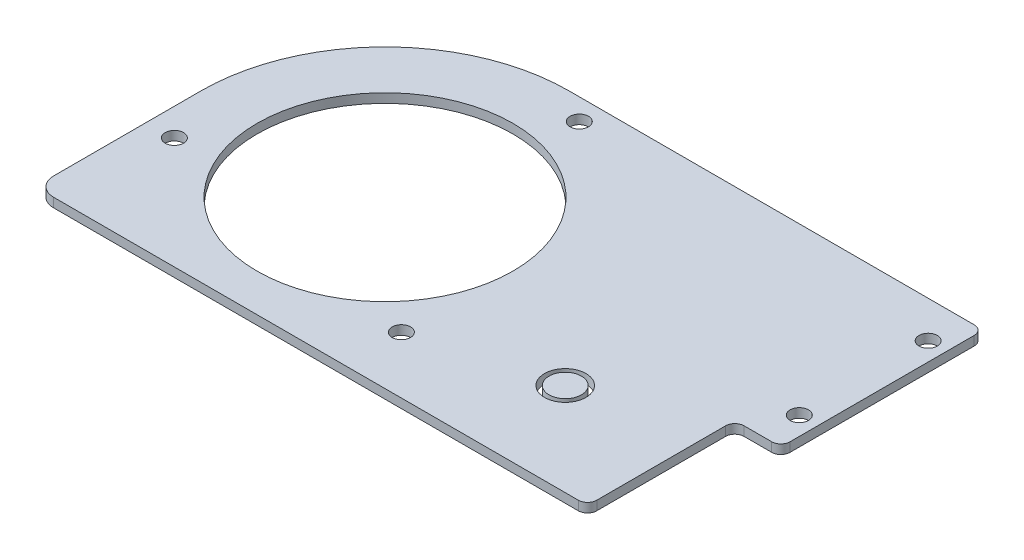
SolidWorks part; units mm, degrees
ref_plane "Front Plane" through (0, 0, 0) normal (0, 0, 1) x (1, 0, 0)
ref_plane "Top Plane" through (0, 0, 0) normal (0, 1, 0) x (1, 0, 0)
ref_plane "Right Plane" through (0, 0, 0) normal (1, 0, 0) x (0, 0, -1)
sketch "Sketch1" plane through (0, 0, 0) normal (0, 1, 0) x (1, 0, 0)
  line L0 (0, 114.3) -> (0, -101.6) construction
  line L1 (279.4, 127) -> (0, 127)
  line L2 (285.75, 120.65) -> (285.75, -6.35)
  line L3 (247.65, -114.3) -> (-114.3, -114.3)
  line L4 (-127, 0) -> (-127, -101.6)
  line L5 (260.35, -12.7) -> (279.4, -12.7)
  line L6 (273.05, -12.7) -> (273.05, 127) construction
  line L7 (-127, 0) -> (285.75, 0) construction
  line L8 (0, 0) -> (-127, -43.7296) construction
  line L11 (254, -107.95) -> (254, -19.05)
  circle A0 centre (0, 0) radius 88.265
  circle A1 centre (0, 0) radius 114.3 construction
  circle A2 centre (-108.0728, -37.2124) radius 6.35
  arc A3 (260.35, -12.7) -> (254, -19.05) centre (260.35, -19.05) ccw
  arc A4 (-127, 0) -> (0, 127) centre (0, 0) cw
  circle A5 centre (21.8095, 112.2) radius 6.35
  circle A6 centre (86.2633, -74.9875) radius 6.35
  arc A7 (-114.3, -114.3) -> (-127, -101.6) centre (-114.3, -101.6) cw
  arc A8 (247.65, -114.3) -> (254, -107.95) centre (247.65, -107.95) ccw
  arc A9 (285.75, -6.35) -> (279.4, -12.7) centre (279.4, -6.35) cw
  arc A10 (279.4, 127) -> (285.75, 120.65) centre (279.4, 120.65) cw
  circle A11 centre (273.05, 101.6) radius 6.35
  circle A12 centre (273.05, 12.7) radius 6.35
  point P0 (0, 0)
  point P11 (0, 0)
  point P32 (254, -114.3)
  point P46 (0, 0)
  dimension "D3" = 176.53
  dimension "D5" = 228.6
  dimension "D6" = 12.7
  dimension "D7" = 127
  dimension "D8" = 101.6
  dimension "D11" = 31.75
  dimension "D12" = 25.4
  dimension "D14" = 12.7
  dimension "D9" = 6.35
  dimension "D10" = 12.7
  dimension "D1" = 127
  dimension "D2" = 114.3
  dimension "D4" = 19
  dimension "D13" = 12.7
  dimension "D15" = 25.4
  dimension "D16" = 412.75
extrude "Boss-Extrude1" add sketch "Sketch1" along normal blind 6.35
sketch "Sketch3" plane through (0, 6.35, 0) normal (0, 1, 0) x (1, 0, 0)
  line L0 (79.375, 127) -> (79.375, -114.3) construction
  line L5 (382.3904, 6.35) -> (-202.4477, 6.35) construction
  line L6 (339.725, -158.75) -> (-180.975, -158.75)
  line L7 (339.725, -158.75) -> (339.725, 171.45)
  line L8 (339.725, 171.45) -> (-180.975, 171.45)
  line L9 (-180.975, -158.75) -> (-180.975, 171.45)
  line L10 (339.725, -158.75) -> (-180.975, 171.45) construction
  line L11 (339.725, 171.45) -> (-180.975, -158.75) construction
  line L26 (285.75, -6.35) -> (285.75, 120.65) construction
  line L27 (-127, 0) -> (-127, -101.6) construction
  line L28 (-114.3, -114.3) -> (247.65, -114.3) construction
  line L29 (279.4, 127) -> (0, 127) construction
  line L30 (285.75, -6.35) -> (285.75, 120.65)
  line L31 (-127, 0) -> (-127, -101.6)
  line L32 (-114.3, -114.3) -> (247.65, -114.3)
  line L33 (279.4, 127) -> (0, 127)
  point P1 (79.375, 6.35)
  dimension "D1" = 520.7
  dimension "D2" = 206.375
  dimension "D3" = 330.2
  dimension "D4" = 120.65
  dimension "D7" = 412.75
  dimension "D8" = 241.3
sketch "Sketch5" plane through (0, 0, 0) normal (0, 1, 0) x (1, 0, 0)
  circle A1 centre (162.3238, 0) radius 11.176 construction
sketch "Sketch6" plane through (0, 0, 0) normal (0, 1, 0) x (1, 0, 0)
  circle A0 centre (174.6148, -50.292) radius 14.2875
  circle A1 centre (174.6148, -50.292) radius 11.176 construction
  circle A2 centre (174.6148, -50.292) radius 11.176
  dimension "D1" = 28.575
extrude "Cut-Extrude1" cut sketch "Sketch6" along normal blind 28.448
